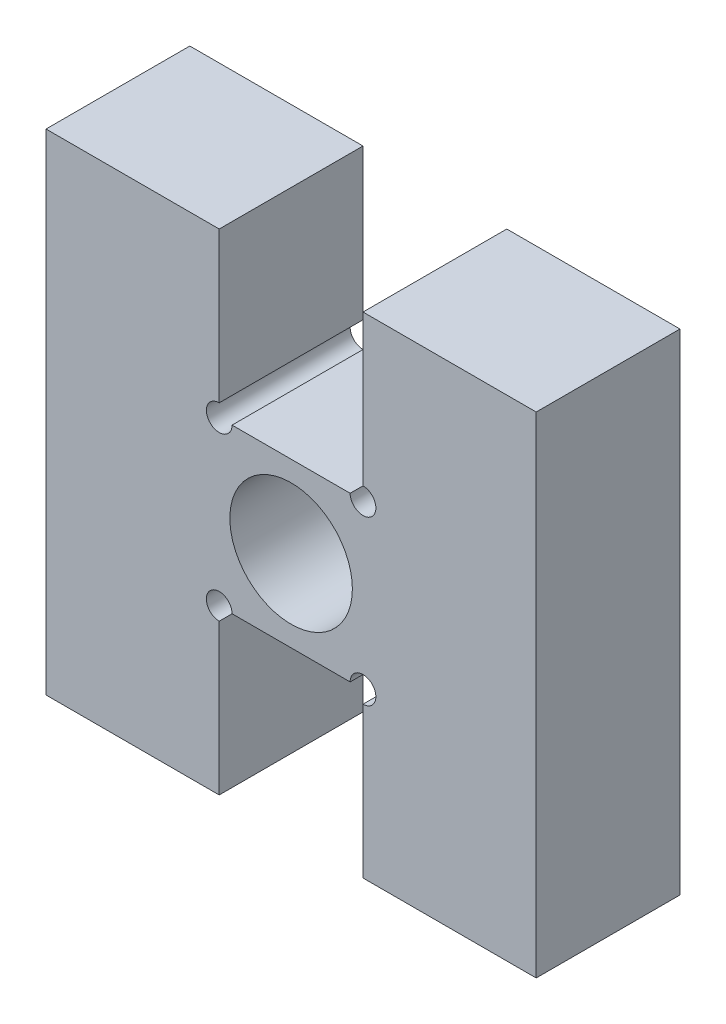
SolidWorks part; units mm, degrees
ref_plane "Front Plane" through (0, 0, 0) normal (0, 0, 1) x (1, 0, 0)
ref_plane "Top Plane" through (0, 0, 0) normal (0, 1, 0) x (1, 0, 0)
ref_plane "Right Plane" through (0, 0, 0) normal (1, 0, 0) x (0, 0, -1)
sketch "Sketch1" plane through (0, 0, 0) normal (0, 0, 1) x (1, 0, 0)
  line L0 (-2.794, 3.175) -> (-2.794, 9.525)
  line L1 (-2.794, 3.175) -> (2.794, 3.175)
  line L3 (-2.794, -3.175) -> (2.794, -3.175)
  line L5 (-2.794, 9.525) -> (-9.525, 9.525)
  line L6 (-9.525, 9.525) -> (-9.525, -9.525)
  line L7 (-9.525, -9.525) -> (-2.794, -9.525)
  line L8 (-2.794, -9.525) -> (-2.794, -3.175)
  line L9 (2.794, -3.175) -> (2.794, -9.525)
  line L10 (2.794, -9.525) -> (9.525, -9.525)
  line L11 (9.525, -9.525) -> (9.525, 9.525)
  line L12 (9.525, 9.525) -> (2.794, 9.525)
  line L13 (2.794, 9.525) -> (2.794, 3.175)
  line L14 (0, 3.175) -> (0, -3.175) construction
  circle A0 centre (0, 0) radius 2.3813
  dimension "D5" = 4.7625
  dimension "D1" = 5.588
  dimension "D2" = 19.05
  dimension "D3" = 19.05
  dimension "D4" = 6.35
extrude "Boss-Extrude1" add sketch "Sketch1" along normal blind 5.588
sketch "Sketch2" plane through (0, 0, 0) normal (0, 0, 1) x (1, 0, 0)
  circle A0 centre (-2.794, 3.175) radius 0.5
  circle A1 centre (2.794, 3.175) radius 0.5
  circle A2 centre (2.794, -3.175) radius 0.5
  circle A3 centre (-2.794, -3.175) radius 0.5
  dimension "D1" = 1
extrude "Cut-Extrude2" cut sketch "Sketch2" along normal through all both and the other way through all
